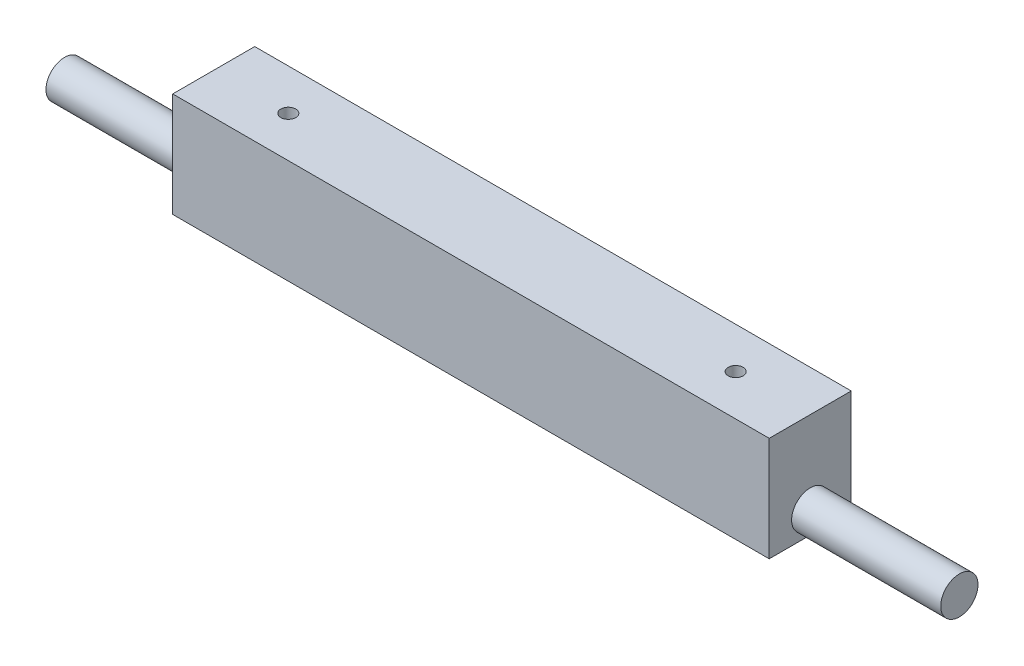
SolidWorks part; units mm, degrees
material "1060 Alloy"
ref_plane "Front Plane" through (0, 0, 0) normal (0, 0, 1) x (1, 0, 0)
ref_plane "Top Plane" through (0, 0, 0) normal (0, 1, 0) x (1, 0, 0)
ref_plane "Right Plane" through (0, 0, 0) normal (1, 0, 0) x (0, 0, -1)
sketch "Sketch2" plane through (0, 0, 0) normal (1, 0, 0) x (0, 0, -1)
  circle A0 centre (0, 0) radius 12.5
  dimension "D1" = 25
extrude "Boss-Extrude1" add sketch "Sketch2" along normal mid plane 600
sketch "Sketch3" plane through (0, 0, 0) normal (1, 0, 0) x (0, 0, -1)
  line L0 (13.75, 0) -> (-13.75, 0) construction
  line L1 (-27.5, 55) -> (27.5, 55)
  line L2 (-27.5, 55) -> (-27.5, -15)
  line L3 (-27.5, -15) -> (27.5, -15)
  line L4 (27.5, 55) -> (27.5, -15)
  line L6 (0, 55) -> (0, -15) construction
  line L7 (0, 13.75) -> (0, -13.75) construction
  dimension "D1" = 55
  dimension "D2" = 55
  dimension "D4" = 15
extrude "Boss-Extrude2" add sketch "Sketch3" along normal mid plane 400
sketch "Sketch4" plane through (0, 55, 0) normal (0, 1, 0) x (1, 0, 0)
  line L0 (-38.5, 0) -> (38.5, 0) construction
  line L1 (0, -30.25) -> (0, 30.25) construction
  circle A0 centre (150, 0) radius 5
  circle A1 centre (-150, 0) radius 5
  dimension "D1" = 10
  dimension "D2" = 150
extrude "Cut-Extrude1" cut sketch "Sketch4" against normal through all
